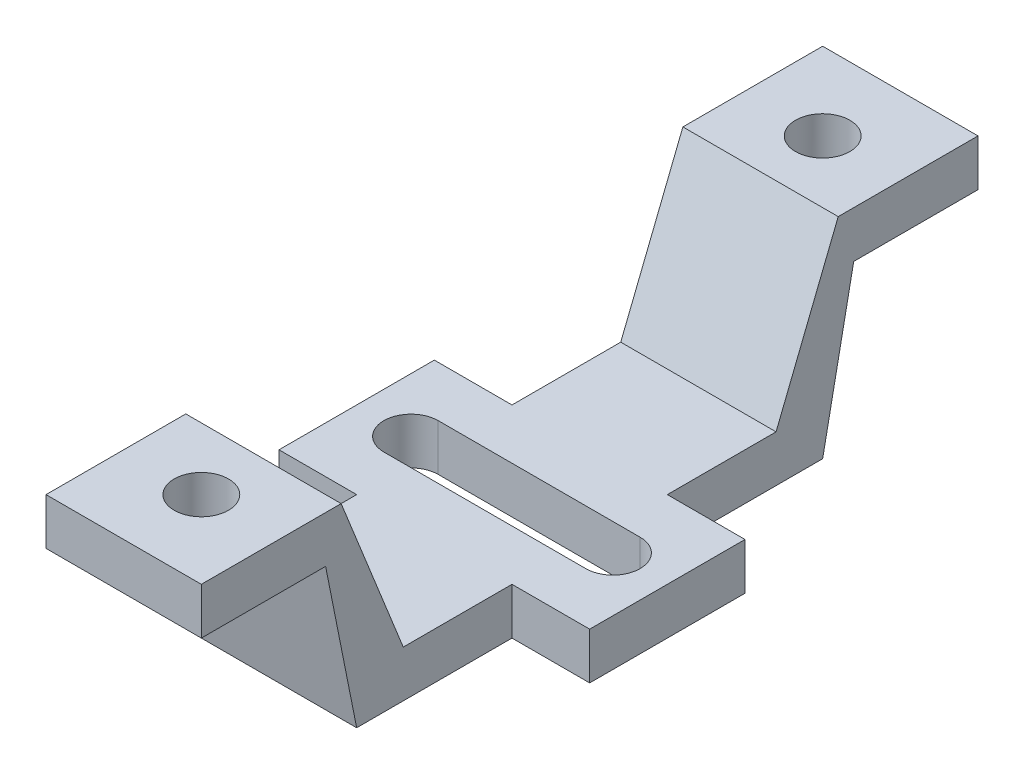
SolidWorks part; units mm, degrees
ref_plane "前视基准面" through (0, 0, 0) normal (0, 0, 1) x (1, 0, 0)
ref_plane "上视基准面" through (0, 0, 0) normal (0, 1, 0) x (1, 0, 0)
ref_plane "右视基准面" through (0, 0, 0) normal (1, 0, 0) x (0, 0, -1)
sketch "草图1" plane through (0, 0, 0) normal (0, 1, 0) x (1, 0, 0)
  line L0 (6.5, 0) -> (-6.5, 0) construction
  line L7 (10, 5) -> (-10, 5)
  line L8 (10, 5) -> (10, -5)
  line L9 (10, -5) -> (-10, -5)
  line L10 (-10, 5) -> (-10, -5)
  line L11 (10, 5) -> (-10, -5) construction
  line L12 (10, -5) -> (-10, 5) construction
  line L13 (-6.5, 1.75) -> (6.5, 1.75)
  line L14 (6.5, -1.75) -> (-6.5, -1.75)
  circle A0 centre (-6.5, 0) radius 1.75
  circle A1 centre (6.5, 0) radius 1.75
  point P0 (0, 0)
  point P2 (-16.0821, 0.9434)
  point P4 (0, 0)
  point P6 (0, 0)
  point P14 (0, 0)
  point P20 (7.1144, -1.75)
  point P21 (-7.1144, -1.75)
  point P22 (7.1144, 1.75)
  dimension "D5" = 3.5
  dimension "D6" = 3.5
  dimension "D3" = 10
  dimension "D4" = 20
  dimension "D7" = 13
extrude "凸台-拉伸1" add sketch "草图1" along normal blind 3 contours L7 L10 L9 L8 A1 L14 A0 L13
sketch "草图2" plane through (0, 0, 0) normal (1, 0, 0) x (0, 0, -1)
  line L0 (0, 3) -> (0, 13) construction
  line L1 (-25, 13) -> (25, 13) construction
  line L2 (-25, 13) -> (-25, 10)
  line L3 (-25, 10) -> (-17, 10)
  line L4 (-5, 0) -> (5, 0)
  line L5 (5, 0) -> (5, 3)
  line L6 (5, 3) -> (-5, 3)
  line L7 (-5, 3) -> (-5, 0)
  line L8 (-5, 0) -> (5, 0)
  line L9 (5, 0) -> (5, 3)
  line L10 (5, 3) -> (-5, 3)
  line L11 (-5, 3) -> (-5, 0)
  line L12 (-25, 13) -> (-17, 13)
  line L13 (-17, 13) -> (-17, 10)
  line L14 (25, 13) -> (25, 10)
  line L15 (25, 10) -> (17, 10)
  line L16 (17, 10) -> (17, 13)
  line L17 (17, 13) -> (25, 13)
  line L18 (-17, 10) -> (-15, 0)
  line L19 (-15, 0) -> (-5, 0)
  line L20 (5, 0) -> (15, 0)
  line L21 (15, 0) -> (17, 10)
  line L22 (-17, 13) -> (-16, 13)
  line L23 (-16, 13) -> (-12, 3)
  line L24 (-12, 3) -> (-5, 3)
  line L25 (5, 3) -> (12, 3)
  line L26 (12, 3) -> (16, 13)
  line L27 (16, 13) -> (17, 13)
  point P10 (0, 13)
  dimension "D2" = 10
  dimension "D3" = 50
  dimension "D4" = 8
  dimension "D5" = 8
  dimension "D6" = 3
  dimension "D7" = 3
  dimension "D8" = 1
  dimension "D9" = 1
  dimension "D10" = 10
  dimension "D11" = 10
  dimension "D12" = 7
  dimension "D13" = 7
  dimension "D1" = 0
extrude "凸台-拉伸2" add sketch "草图2" along normal mid plane 10 contours L13 L12 L2 L3 | L24 L23 L22 L13 L18 L19 L11 | L27 L26 L25 L9 L20 L21 L16 | L17 L16 L15 L14
sketch "草图3" plane through (0, 13, 0) normal (0, 1, 0) x (1, 0, 0)
  line L0 (0, -20) -> (0, 20) construction
  circle A0 centre (0, 20) radius 1.75
  circle A1 centre (0, -20) radius 1.75
  point P4 (0, -20.5)
  point P8 (0, 0)
  dimension "D1" = 3.5
  dimension "D2" = 3.5
  dimension "D3" = 40
extrude "切除-拉伸1" cut sketch "草图3" against normal blind 10
